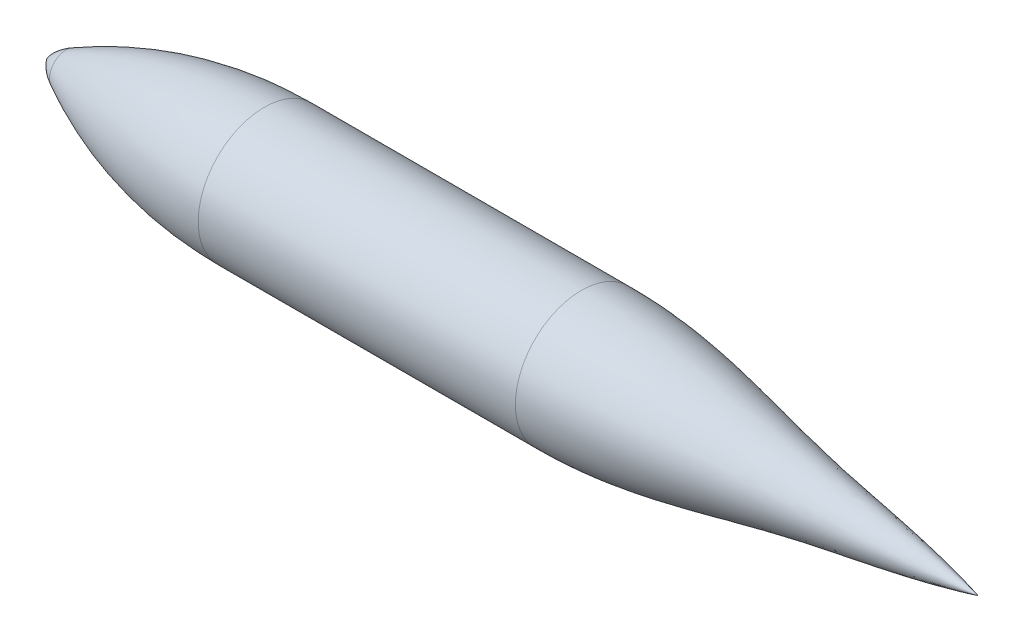
SolidWorks part; units mm, degrees
material "3003-H14"
ref_plane "Piano frontale" through (0, 0, 0) normal (1, 0, 0) x (0, 1, 0)
ref_plane "Piano superiore" through (0, 0, 0) normal (0, 0, 1) x (0, 1, 0)
ref_plane "Piano destro" through (0, 0, 0) normal (0, 1, 0) x (-1, 0, 0)
sketch "Schizzo6" plane through (0, 0, 0) normal (0, 1, 0) x (-1, 0, 0)
  line L0 (312.8, 28.97) -> (173.8, 28.97)
  line L1 (0, 0) -> (407.9842, 0)
  spline S0 degree 2 poles (312.8, 28.97) (358.929, 28.7786) (399.7, 7.24) knots 0 0 0 1 1 1
  spline S1 degree 2 poles (399.7, 7.24) (404.7781, 4.6847) (407.9842, 0) knots 0 0 0 1 1 1
  spline S2 degree 3 poles (0, 0) (25.1897, 6.7516) (65.5245, 11.0779) (123.6018, 24.779) (154.2741, 28.97) (173.8, 28.97) knots 0 0 0 0 0.440523 0.69482 1 1 1 1
  point P0 (0, 0)
  point P1 (312.8, 28.97)
  point P3 (173.8, 28.97)
  point P4 (399.7, 7.24)
  point P7 (203.9921, 0)
  point P13 (0, 0)
  point P15 (0, 0)
  dimension "D1" = 173.8
  dimension "D2" = 399.7
  dimension "D3" = 312.8
  dimension "D4" = 28.97
  dimension "D5" = 7.24
  dimension "D6" = 28.97
revolve "Rivoluzione1" add sketch "Schizzo6" angle 360 about L1
equation "\"D\"= 182 / pi"
equation "\"R\"= \"D\" / 2"
equation "\"NoseRatio\"= 3"
equation "\"L_cyl\"= 139"
equation "\"L_nose\"= \"NoseRatio\" * \"D\""
equation "\"L_total\"= \"L_nose\" + \"L_cyl\""
equation "\"TailRatio\"= 1.5"
equation "\"L_tail\"= \"TailRatio\" * \"D\""
equation "\"R_tip\"= 0.03 * \"D\""
